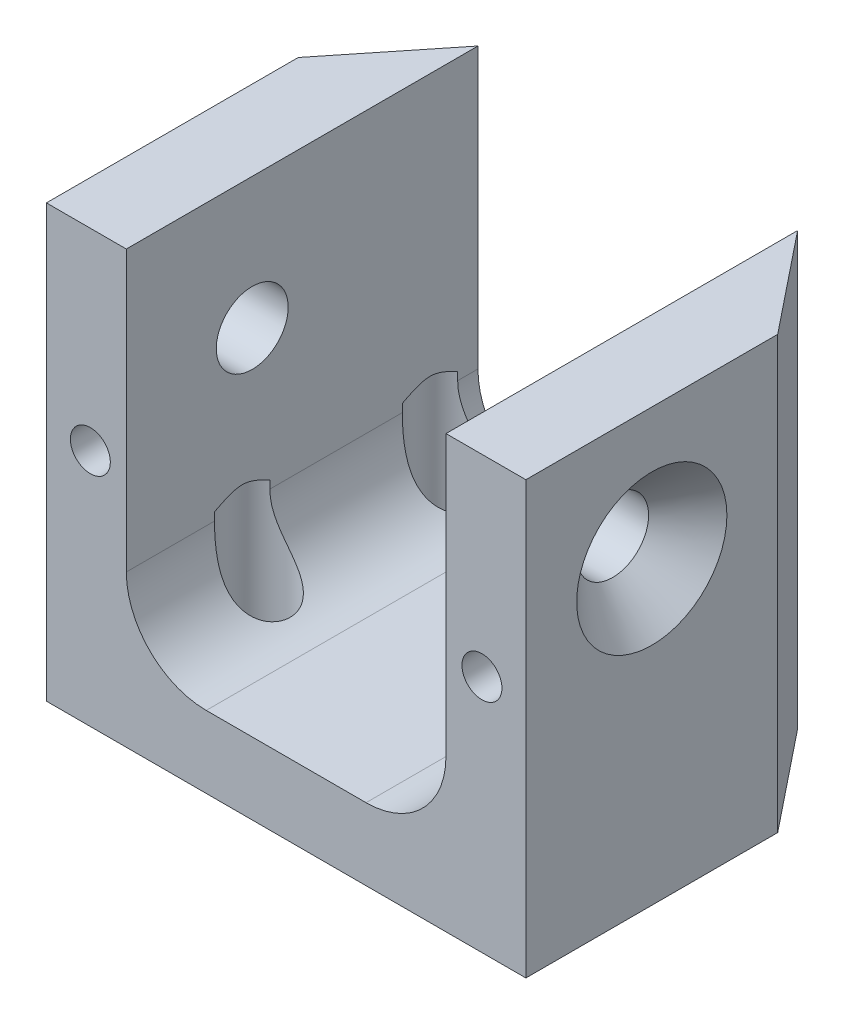
SolidWorks part; units mm, degrees
ref_plane "Front Plane" through (0, 0, 0) normal (0, 0, 1) x (1, 0, 0)
ref_plane "Top Plane" through (0, 0, 0) normal (0, 1, 0) x (1, 0, 0)
ref_plane "Right Plane" through (0, 0, 0) normal (1, 0, 0) x (0, 0, -1)
sketch "Sketch1" plane through (0, 0, 0) normal (0, 1, 0) x (1, 0, 0)
  line L0 (0, 0) -> (0, 15.755)
  line L1 (0, 15.755) -> (5, 22)
  line L2 (5, 22) -> (25, 22)
  line L3 (25, 22) -> (30, 15.755)
  line L4 (30, 15.755) -> (30, 0)
  line L5 (30, 0) -> (0, 0)
  point P3 (15, 0)
  point P8 (15, 22)
  dimension "D1" = 30
  dimension "D2" = 22
  dimension "D3" = 8
  dimension "D4" = 8
  dimension "D5" = 20
extrude "Boss-Extrude1" add sketch "Sketch1" along normal blind 27
sketch "Sketch2" plane through (0, 0, 0) normal (0, 0, 1) x (1, 0, 0)
  line L0 (0, 0) -> (30, 0) construction
  line L1 (5, 27) -> (25, 27)
  line L2 (5, 27) -> (5, 4.5)
  line L3 (5, 4.5) -> (25, 4.5)
  line L4 (25, 27) -> (25, 4.5)
  line L7 (0, 27) -> (30, 27) construction
  point P6 (15, 0)
  dimension "D1" = 4.5
extrude "Cut-Extrude1" cut sketch "Sketch2" against normal up to vertex (22 mm away)
sketch "Sketch3" plane through (0, 0, 0) normal (0, 0, 1) x (1, 0, 0)
  line L0 (5, 9.5) -> (5, 4.5)
  line L1 (5, 27) -> (5, 4.5) construction
  line L2 (5, 4.5) -> (10, 4.5)
  line L3 (5, 4.5) -> (25, 4.5) construction
  line L4 (25, 9.5) -> (25, 4.5)
  line L5 (25, 4.5) -> (25, 27) construction
  line L6 (25, 4.5) -> (20, 4.5)
  arc A0 (5, 9.5) -> (10, 4.5) centre (10, 9.5) ccw
  arc A1 (20, 4.5) -> (25, 9.5) centre (20, 9.5) ccw
  dimension "D1" = 10
extrude "Boss-Extrude2" add sketch "Sketch3" against normal up to vertex (22 mm away)
ref_plane "Plane1" through (30, 0, 0) normal (1, 0, 0) x (0, 0, -1)
hole_wizard "CSK for M4 Countersunk Flat Head Screw1" positions "Sketch6" profile "Sketch7" countersink size "M4" standard "ISO"
sketch "Sketch6" plane through (30, 0, 0) normal (1, 0, 0) x (0, 0, -1)
  line L0 (0, 27) -> (15.755, 27) construction
  point P0 (7.8775, 18.7869)
  point P7 (7.8775, 27)
  dimension "D1" = 8.2131
sketch "Sketch7" plane through (30, 18.7869, -7.8775) normal (0, 1, 0) x (0, 0, -1)
  line L0 (0, 0) -> (0, 36.3519)
  line L1 (0, 36.3519) -> (2.25, 35)
  line L2 (2.25, 35) -> (2.25, 2.45)
  line L3 (2.25, 2.45) -> (4.7, 0)
  line L5 (4.7, 0) -> (0, 0)
  line L6 (-2.25, 2.45) -> (-4.7, 0) construction
  line L10 (0, 36.3519) -> (-2.25, 35) construction
  line L11 (0, -6.35) -> (0, 107.95) construction
  dimension "Hole Dia." = 4.5
  dimension "Hole Depth" = 35
  dimension "Near C'Sink Dia." = 9.4
  dimension "Near C'Sink Angle" = 90
  dimension "Drill Angle" = 118
hole_wizard "Ø2.5mm Dowel Hole1" positions "Sketch8" profile "Sketch9" hole size "Ø2.5" standard "ANSI Metric"
sketch "Sketch8" plane through (0, 0, 0) normal (0, 0, 1) x (1, 0, 0)
  line L0 (0, 27) -> (0, 0) construction
  line L1 (30, 27) -> (30, 0) construction
  line L2 (0, 27) -> (5, 27) construction
  point P0 (2.75, 14.95)
  point P2 (27.25, 14.95)
  point P13 (3.7114, 34.9769)
  point P14 (0, 0)
  point P17 (0, 0)
  dimension "D1" = 2.75
  dimension "D2" = 2.75
  dimension "D3" = 12.05
sketch "Sketch9" plane through (2.75, 14.95, 0) normal (1, 0, 0) x (0, -1, 0)
  line L0 (0, 0) -> (0, 10.7511)
  line L1 (0, 10.7511) -> (1.25, 10)
  line L2 (1.25, 10) -> (1.25, 0)
  line L5 (1.25, 0) -> (0, 0)
  line L10 (0, 10.7511) -> (-1.25, 10) construction
  line L11 (0, -6.35) -> (0, 107.95) construction
  dimension "Hole Dia." = 2.5
  dimension "Hole Depth" = 10
  dimension "Drill Angle" = 118
hole_wizard "Ø4.0mm Dowel Hole1" positions "Sketch12" profile "Sketch13" hole size "Ø4.0" standard "ANSI Metric"
sketch "Sketch12" plane through (0, 0, 0) normal (0, -1, 0) x (-1, 0, 0)
  line L4 (-30, 0) -> (-30, 15.755) construction
  line L6 (0, 15.755) -> (0, 0) construction
  line L7 (-20, 22) -> (-25, 22) construction
  point P0 (-24, 19)
  point P2 (-6, 19)
  point P4 (-6, 7.25)
  point P6 (-24, 7.25)
  point P31 (0, 0)
  dimension "D1" = 11.75
  dimension "D2" = 3
  dimension "D3" = 6
  dimension "D4" = 6
sketch "Sketch13" plane through (24, 0, -19) normal (1, 0, 0) x (0, 0, -1)
  line L0 (0, 0) -> (0, 11.2017)
  line L1 (0, 11.2017) -> (2, 10)
  line L2 (2, 10) -> (2, 0)
  line L5 (2, 0) -> (0, 0)
  line L10 (0, 11.2017) -> (-2, 10) construction
  line L11 (0, -6.35) -> (0, 107.95) construction
  dimension "Hole Dia." = 4
  dimension "Hole Depth" = 10
  dimension "Drill Angle" = 118
